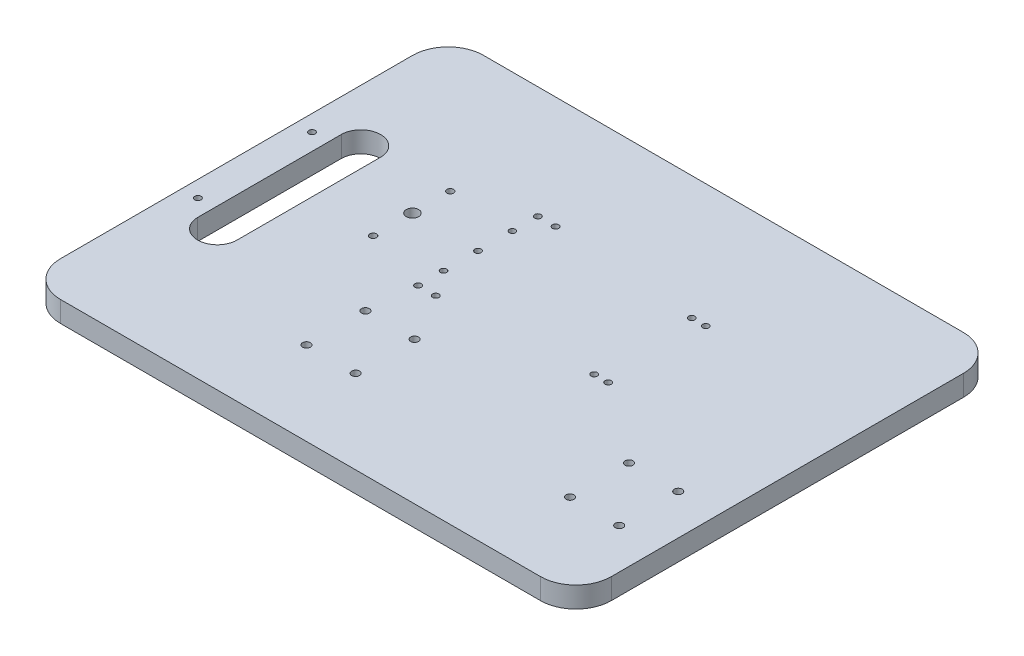
SolidWorks part; units mm, degrees
ref_plane "Front Plane" through (0, 0, 0) normal (0, 0, 1) x (1, 0, 0)
ref_plane "Top Plane" through (0, 0, 0) normal (0, 1, 0) x (1, 0, 0)
ref_plane "Right Plane" through (0, 0, 0) normal (1, 0, 0) x (0, 0, -1)
sketch "Sketch1" plane through (0, 0, 0) normal (0, 1, 0) x (1, 0, 0)
  line L1 (140, -107.5) -> (-140, -107.5)
  line L2 (140, -107.5) -> (140, 107.5)
  line L3 (140, 107.5) -> (-140, 107.5)
  line L4 (-140, -107.5) -> (-140, 107.5)
  line L5 (140, -107.5) -> (-140, 107.5) construction
  line L6 (140, 107.5) -> (-140, -107.5) construction
  point P0 (0, 0)
  dimension "D1" = 215
  dimension "D2" = 280
extrude "Boss-Extrude1" add sketch "Sketch1" along normal blind 10.6
fillet "Fillet1" radius 18 4 edges at (-140, 5.3, -107.5) (140, 5.3, -107.5) (140, 5.3, 107.5) (-140, 5.3, 107.5)
sketch "Sketch2" plane through (0, 10.6, 0) normal (0, 1, 0) x (1, 0, 0)
  line L0 (-113.3, 107.5) -> (-113.3, -107.5) construction
  line L1 (122, 107.5) -> (-122, 107.5) construction
  line L2 (-122, -107.5) -> (122, -107.5) construction
  line L3 (-113.3, -36.5) -> (-113.3, 36.5) construction
  line L4 (-123.3, -36.5) -> (-123.3, 36.5)
  line L5 (-103.3, -36.5) -> (-103.3, 36.5)
  line L6 (-140, 89.5) -> (-140, -89.5) construction
  arc A0 (-123.3, -36.5) -> (-103.3, -36.5) centre (-113.3, -36.5) ccw
  arc A1 (-103.3, 36.5) -> (-123.3, 36.5) centre (-113.3, 36.5) ccw
  point P8 (-113.3, 0)
  dimension "D3" = 93
  dimension "D1" = 16.7
  dimension "D2" = 20
extrude "Cut-Extrude1" cut sketch "Sketch2" against normal through all
sketch "Sketch3" plane through (0, 10.6, 0) normal (0, 1, 0) x (1, 0, 0)
  line L2 (-72.3, 40) -> (-72.3, 38.4)
  line L3 (-68.9, 38.4) -> (-68.9, 40)
  line L4 (-72.3, 40) -> (-72.3, 38.4) construction
  line L5 (-68.9, 38.4) -> (-68.9, 40) construction
  line L6 (52.8, 43.2) -> (54.6, 43.2)
  line L7 (54.6, 46.4) -> (52.8, 46.4)
  line L8 (52.8, 43.2) -> (54.6, 43.2) construction
  line L9 (54.6, 46.4) -> (52.8, 46.4) construction
  line L10 (54.6, -3.2) -> (52.8, -3.2)
  line L11 (52.8, -6.4) -> (54.6, -6.4)
  line L12 (54.6, -3.2) -> (52.8, -3.2) construction
  line L13 (52.8, -6.4) -> (54.6, -6.4) construction
  line L15 (-12, -63) -> (-42, -63)
  line L16 (-42, -67) -> (-12, -67)
  line L17 (-12, -63) -> (-42, -63) construction
  line L18 (-42, -67) -> (-12, -67) construction
  line L20 (92, -67) -> (122, -67)
  line L21 (122, -63) -> (92, -63)
  line L22 (92, -67) -> (122, -67) construction
  line L23 (122, -63) -> (92, -63) construction
  line L24 (-70.6, 40) -> (-70.6, 38.4) construction
  line L25 (92, -37) -> (122, -37)
  line L26 (122, -33) -> (92, -33)
  line L27 (92, -37) -> (122, -37) construction
  line L28 (122, -33) -> (92, -33) construction
  line L29 (52.8, 44.8) -> (54.6, 44.8) construction
  line L30 (-12, -33) -> (-42, -33)
  line L31 (-42, -37) -> (-12, -37)
  line L32 (-12, -33) -> (-42, -33) construction
  line L33 (-42, -37) -> (-12, -37) construction
  line L34 (52.8, -4.8) -> (54.6, -4.8) construction
  line L35 (92, -35) -> (122, -35) construction
  line L36 (-42, -35) -> (-12, -35) construction
  line L37 (-42, -65) -> (-12, -65) construction
  line L38 (92, -65) -> (122, -65) construction
  line L39 (-39.5, -35) -> (-39.5, -65) construction
  line L40 (-14.5, -35) -> (-14.5, -65) construction
  line L41 (94.5, -35) -> (94.5, -65) construction
  line L42 (119.5, -35) -> (119.5, -65) construction
  line L43 (-27, -63) -> (-39.5, -65) construction
  line L44 (-27, -63) -> (-14.5, -65) construction
  line L45 (107, -67) -> (94.5, -65) construction
  line L46 (107, -67) -> (119.5, -65) construction
  circle A0 centre (-131.75, -27.9) radius 1.6 construction
  circle A1 centre (-131.75, 30.1) radius 1.6 construction
  circle A2 centre (-131.75, -27.9) radius 1.6
  circle A3 centre (-131.75, 30.1) radius 1.6
  circle A4 centre (-70.6, 20) radius 3.15 construction
  circle A5 centre (-70.6, 20) radius 3.15
  circle A6 centre (-70.6, 0) radius 1.7 construction
  circle A7 centre (-70.6, 0) radius 1.7
  circle A9 centre (-28.3, -10.4427) radius 1.6 construction
  circle A10 centre (-37.3, -10.4427) radius 1.6 construction
  arc A11 (-72.3, 38.4) -> (-68.9, 38.4) centre (-70.6, 38.4) ccw
  arc A12 (-68.9, 40) -> (-72.3, 40) centre (-70.6, 40) ccw
  arc A13 (-72.3, 38.4) -> (-68.9, 38.4) centre (-70.6, 38.4) ccw construction
  arc A14 (-68.9, 40) -> (-72.3, 40) centre (-70.6, 40) ccw construction
  circle A15 centre (-37.3, 2.5) radius 1.55 construction
  circle A16 centre (-37.3, 20) radius 1.6 construction
  circle A17 centre (-37.3, 37.5) radius 1.55 construction
  circle A18 centre (-28.3, 50.4427) radius 1.6 construction
  circle A19 centre (-37.3, 50.4427) radius 1.6 construction
  circle A20 centre (-28.3, -10.4427) radius 1.6
  circle A21 centre (-37.3, -10.4427) radius 1.6
  circle A22 centre (-37.3, 2.5) radius 1.55
  circle A23 centre (-37.3, 20) radius 1.6
  circle A24 centre (-37.3, 37.5) radius 1.55
  circle A25 centre (-28.3, 50.4427) radius 1.6
  circle A26 centre (-37.3, 50.4427) radius 1.6
  circle A27 centre (46.6, -4.8) radius 1.6 construction
  circle A28 centre (46.6, 44.8) radius 1.6 construction
  circle A29 centre (46.6, -4.8) radius 1.6
  circle A30 centre (46.6, 44.8) radius 1.6
  circle A31 centre (-70.6, 39.2) radius 1.7
  circle A32 centre (53.7, 44.8) radius 1.6
  arc A33 (52.8, 46.4) -> (52.8, 43.2) centre (52.8, 44.8) ccw
  arc A34 (54.6, 43.2) -> (54.6, 46.4) centre (54.6, 44.8) ccw
  arc A35 (52.8, 46.4) -> (52.8, 43.2) centre (52.8, 44.8) ccw construction
  arc A36 (54.6, 43.2) -> (54.6, 46.4) centre (54.6, 44.8) ccw construction
  arc A37 (52.8, -3.2) -> (52.8, -6.4) centre (52.8, -4.8) ccw
  arc A38 (54.6, -6.4) -> (54.6, -3.2) centre (54.6, -4.8) ccw
  arc A39 (52.8, -3.2) -> (52.8, -6.4) centre (52.8, -4.8) ccw construction
  arc A40 (54.6, -6.4) -> (54.6, -3.2) centre (54.6, -4.8) ccw construction
  arc A41 (-12, -67) -> (-12, -63) centre (-12, -65) ccw
  arc A42 (-42, -63) -> (-42, -67) centre (-42, -65) ccw
  arc A43 (-12, -67) -> (-12, -63) centre (-12, -65) ccw construction
  arc A44 (-42, -63) -> (-42, -67) centre (-42, -65) ccw construction
  arc A45 (92, -63) -> (92, -67) centre (92, -65) ccw
  arc A46 (122, -67) -> (122, -63) centre (122, -65) ccw
  arc A47 (92, -63) -> (92, -67) centre (92, -65) ccw construction
  arc A48 (122, -67) -> (122, -63) centre (122, -65) ccw construction
  arc A49 (92, -33) -> (92, -37) centre (92, -35) ccw
  arc A50 (122, -37) -> (122, -33) centre (122, -35) ccw
  arc A51 (92, -33) -> (92, -37) centre (92, -35) ccw construction
  arc A52 (122, -37) -> (122, -33) centre (122, -35) ccw construction
  arc A53 (-12, -37) -> (-12, -33) centre (-12, -35) ccw
  arc A54 (-42, -33) -> (-42, -37) centre (-42, -35) ccw
  arc A55 (-12, -37) -> (-12, -33) centre (-12, -35) ccw construction
  arc A56 (-42, -33) -> (-42, -37) centre (-42, -35) ccw construction
  circle A57 centre (53.7, -4.8) radius 1.6
  circle A58 centre (-39.5, -35) radius 2
  circle A59 centre (-14.5, -35) radius 2
  circle A60 centre (-39.5, -65) radius 2
  circle A61 centre (-14.5, -65) radius 2
  circle A62 centre (94.5, -35) radius 2
  circle A63 centre (119.5, -35) radius 2
  circle A64 centre (94.5, -65) radius 2
  circle A65 centre (119.5, -65) radius 2
  dimension "D8" = 25
  dimension "D9" = 25
  dimension "D1" = 0
  dimension "D2" = 0
  dimension "D3" = 0
  dimension "D4" = 0
  dimension "D5" = 0
  dimension "D6" = 0
  dimension "D7" = 0
extrude "Cut-Extrude2" cut sketch "Sketch3" against normal through all
